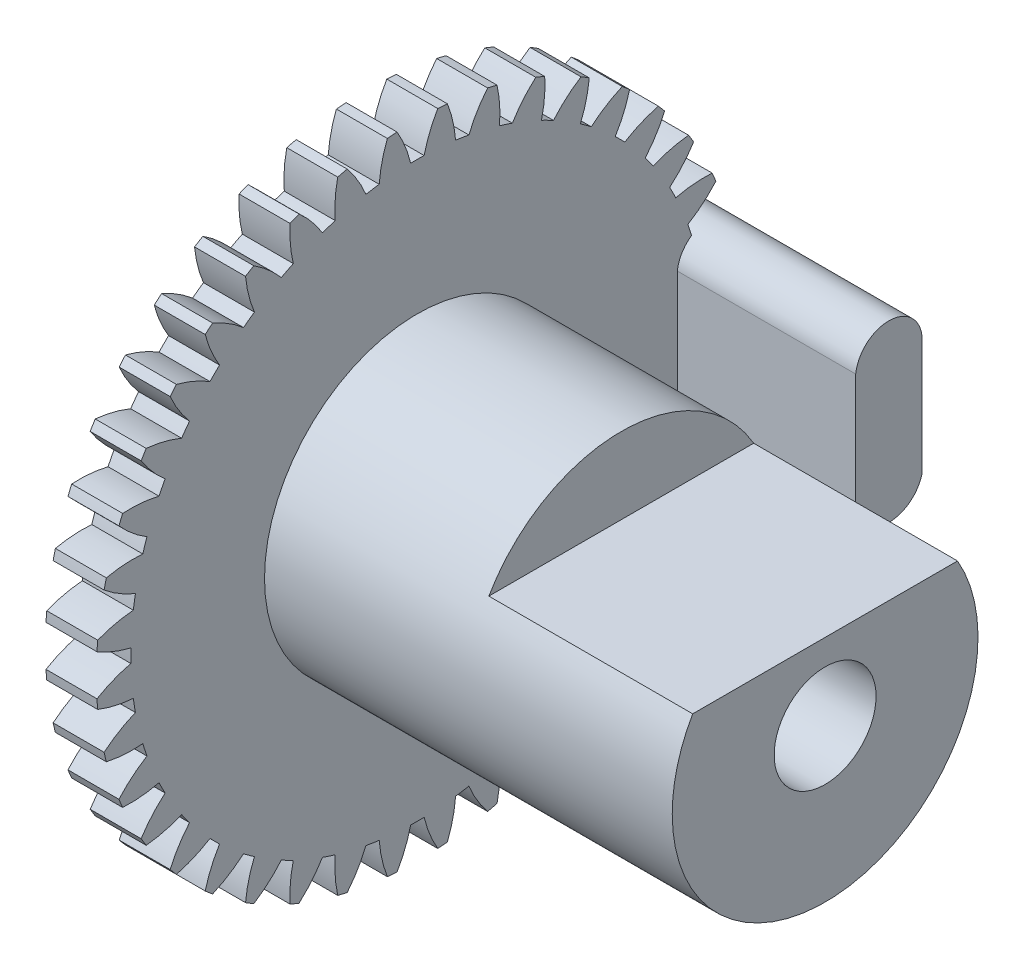
SolidWorks part; units mm, degrees
material "ABS PC"
ref_plane "Plane1" through (0, 0, 0) normal (0, 0, 1) x (1, 0, 0)
ref_plane "Plane2" through (0, 0, 0) normal (0, 1, 0) x (1, 0, 0)
ref_plane "Plane3" through (0, 0, 0) normal (1, 0, 0) x (0, 0, -1)
sketch "HoldingSke" plane through (0, 0, 0) normal (0, 1, 0) x (1, 0, 0)
  line L0 (0, 0) -> (2.5535, -2.1426)
  line L1 (-15, 0) -> (100, 0) construction
  line L2 (0, 0) -> (-2.1039, 2.3779)
  line L3 (0, 0) -> (-11.863, 4.5341)
  line L4 (0, 0) -> (6.6156, 5.5511)
  line L5 (0, 0) -> (-46.8476, -17.4728)
  line L6 (0, 0) -> (-0.829, -0.5593)
  line L7 (-2.1039, 2.3779) -> (8.6586, 51.2059)
  line L8 (-76.2, 54.61) -> (-75.9, 54.61)
  line L9 (-71.009, 38.7566) -> (-53.1078, 45.2721)
  line L10 (-76.2, 71.12) -> (104.1128, 71.12)
  line L11 (0, 0) -> (-1, 0)
  line L12 (-76.2, 101.6) -> (-76.19, 101.6)
  line L13 (24.9733, 27.94) -> (52.9518, 28.4284)
  line L14 (24.9733, 27.94) -> (24.9743, 27.94)
  line L15 (24.9733, 27.94) -> (100.4006, 29.5858)
  line L16 (-63.627, -0.3) -> (-12.827, -0.3)
  circle A0 centre (0, 0) radius 1
  circle A1 centre (0, 0) radius 5.624
  circle A2 centre (0, 0) radius 37.5
  circle A3 centre (0, 0) radius 1
  dimension "MHD" = 11.248
  dimension "Hub_dia" = 75
  dimension "Bore" = 2
  dimension "MBD" = 2
  dimension "Num_teeth" = 40
  dimension "Pitch" = 3.3333
  dimension "Overall_len" = 50
  dimension "Show_teeth" = 40
  dimension "Thickness" = 1
  dimension "OAL" = 50.0001
  dimension "T_dim" = 0.3
  dimension "Ap" = 20
  dimension "H" = 19.05
  dimension "Pitch_radius" = 180.3128
  dimension "Width" = 1
  dimension "Backlash" = 0.01
  dimension "Addendum_fac" = 1
  dimension "Dedendum_fac" = 1.25
  dimension "Clearance_fac" = 0.25
  dimension "Dedendum_add" = 0.001
  dimension "Module" = 0.3
sketch "BasProSke" plane through (0, 0, 0) normal (0, 1, 0) x (1, 0, 0)
  line L0 (-10, 0) -> (60, 0) construction
  line L1 (0, 0) -> (0, 6.3)
  line L2 (0, 0) -> (1, 0)
  line L3 (1, 0) -> (1, 6.3)
  line L4 (1, 6.3) -> (0, 6.3)
  dimension "Thickness" = 1
  dimension "Diameter" = 12.6
revolve "Base-Revolve" add sketch "BasProSke" angle 360 about L0
sketch "TooCutSke" plane through (0, 0, 0) normal (1, 0, 0) x (0, 0, -1)
  line L1 (0, 0) -> (0, 107) construction
  line L2 (0, 0) -> (-0.2531, 5.9947) construction
  line L3 (0, 0) -> (-0.9409, 11.9551) construction
  line L4 (-0.2531, 5.9947) -> (-0.4704, 5.9776) construction
  arc A0 (0.1321, 5.6224) -> (-0.1321, 5.6224) centre (0, 0) ccw
  arc A1 (0.4141, 6.3118) -> (-0.4141, 6.3118) centre (0, 0) ccw
  circle A2 centre (0, 0) radius 6 construction
  circle A3 centre (0, 0) radius 5.6382 construction
  arc A4 (-0.1321, 5.6224) -> (-0.4141, 6.3118) centre (-2.4676, 5.0695) ccw
  arc A5 (0.4141, 6.3118) -> (0.1321, 5.6224) centre (2.4676, 5.0695) ccw
  dimension "Root_dia" = 11.248
  dimension "Overcut_dia" = 12.6508
  dimension "Pitch_dia" = 12
  dimension "Base_dia" = 11.2763
  dimension "Flank_rad" = 2.4
  dimension "Half_ang" = 4.5
  dimension "Half_CT" = 0.2181
extrude "ToothCut" cut sketch "TooCutSke" along normal through all
fillet "Breaks" [suppressed] radius 0.006
fillet "RootFillets" [suppressed] radius 0.076
pattern_circular "TeethCuts" count 40 every 9 about axis through (-10, 0, 0) along (1, 0, 0) of "ToothCut", "RootFillets", "Breaks"
sketch "HubNeaOneSke" plane through (0, 0, 0) normal (-1, 0, 0) x (0, 0, 1)
  circle A0 centre (0, 0) radius 5.624
  dimension "Diameter" = 11.248
extrude "HubNearOne" [suppressed] add sketch "HubNeaOneSke" along normal blind 49.0001
sketch "HubNeaBotSke" plane through (0, 0, 0) normal (-1, 0, 0) x (0, 0, 1)
  circle A0 centre (0, 0) radius 5.624
  dimension "Diameter" = 11.248
extrude "HubNearBoth" [suppressed] add sketch "HubNeaBotSke" along normal blind 24.5
ref_plane "FarPln" through (1, 0, 0) normal (1, 0, 0) x (0, 0, -1)
sketch "HubFarSke" plane through (1, 0, 0) normal (1, 0, 0) x (0, 0, -1)
  circle A0 centre (0, 0) radius 5.624
  dimension "Diameter" = 11.248
extrude "HubFar" [suppressed] add sketch "HubFarSke" along normal blind 24.5
sketch "BorSke" plane through (0, 0, 0) normal (1, 0, 0) x (0, 0, -1)
  circle A0 centre (0, 0) radius 1
  dimension "Diameter" = 2
extrude "Bore" cut sketch "BorSke" along normal mid plane 100.0001
sketch "KeySke" plane through (0, 0, 0) normal (1, 0, 0) x (0, 0, -1)
  line L0 (-0.4, 0) -> (-0.4, 1.3)
  line L1 (-0.4, 1.3) -> (0.4, 1.3)
  line L2 (0.4, 1.3) -> (0.4, 0)
  line L3 (0, 0) -> (0, 34) construction
  line L4 (-0.4, 0) -> (0.4, 0)
  dimension "Offset" = 1.3
  dimension "Width" = 0.8
extrude "Keyway" [suppressed] cut sketch "KeySke" along normal mid plane 100.0001
pattern_circular "Keyway2" [suppressed] count 2 every 90 about axis through (-10, 0, 0) along (1, 0, 0)
sketch "Schizzo1" plane through (1, 0, 0) normal (1, 0, 0) x (0, 0, -1)
  circle A0 centre (0, 0) radius 1
  circle A1 centre (0, 0) radius 3
  circle A2 centre (0, 0) radius 1 construction
  dimension "D1" = 6
extrude "Estrusione-Estrusione1" add sketch "Schizzo1" along normal blind 8
sketch "Schizzo2" plane through (9, 0, 0) normal (1, 0, 0) x (0, 0, -1)
  line L0 (-2.5981, 1.5) -> (2.5981, 1.5)
  circle A0 centre (0, 0) radius 3 construction
  arc A1 (2.5981, 1.5) -> (-2.5981, 1.5) centre (0, 0) ccw
  dimension "D1" = 1.5
extrude "Taglio-Estrusione1" cut sketch "Schizzo2" against normal blind 4
sketch "Schizzo3" plane through (1, 0, 0) normal (1, 0, 0) x (0, 0, -1)
  line L0 (5.75, 1.1) -> (5.75, -1) construction
  line L1 (6.4, 1.1752) -> (6.4, -1.1752)
  line L2 (5.1, 1.1752) -> (5.1, -1.1752)
  line L4 (5.75, 0) -> (0, 0) construction
  arc A0 (6.4, 1.1752) -> (5.1, 1.1752) centre (5.75, 1.1) ccw
  arc A1 (5.1, -1.1752) -> (6.4, -1.1752) centre (5.75, -1) ccw
  point P16 (5.1, 0)
  dimension "D1" = 2.1
  dimension "D2" = 1.3
  dimension "D3" = 5.75
  dimension "D4" = 1
  dimension "D5" = 2.3505
extrude "Estrusione-Estrusione2" add sketch "Schizzo3" along normal blind 4.5 from surface at -1 starting at face at (0, 0, -1)
equation "' \"Module@HoldingSke\" = 6.35"
equation "' \"Num_teeth@HoldingSke\" = 12"
equation "' \"Ap@HoldingSke\" =  20"
equation "' \"Ap@HoldingSke\" = 20"
equation "' \"Width@HoldingSke\" = 0.5 * 25.4"
equation "' \"Hub_dia@HoldingSke\"= 1 * 25.4"
equation "' \"Hub_dia@HoldingSke\" = 1 * 25.4"
equation "' \"Overall_len@HoldingSke\" = 1.0 * 25.4"
equation "' \"Bore@HoldingSke\" = 0.75 * 25.4"
equation "' \"T_dim@HoldingSke\" = 0.1 * 25.4"
equation "' \"Width@KeySke\" = 0.25 * 25.4"
equation "' \"Show_teeth@HoldingSke\" = 13"
equation "' \"Backlash@HoldingSke\" = 0.009 * 25.4"
equation "' \"Addendum_fac@HoldingSke\" = 1.0"
equation "' \"Dedendum_fac@HoldingSke\" = 1.25"
equation "' \"Dedendum_add@HoldingSke\" = 0.00005 * 25.4"
equation "' \"Clearance_fac@HoldingSke\" = 0.25"
equation "\"Pitch@HoldingSke\" = 1 / \"Module@HoldingSke\""
equation "\"Overcut_dia@TooCutSke\" = (\"Num_teeth@HoldingSke\" + 2 * \"Addendum_fac@HoldingSke\") / \"Pitch@HoldingSke\" + 0.002 * 25.4"
equation "\"Pitch_dia@TooCutSke\" = \"Num_teeth@HoldingSke\" / \"Pitch@HoldingSke\""
equation "\"Base_dia@TooCutSke\" = \"Num_teeth@HoldingSke\" / \"Pitch@HoldingSke\" * cos((\"Ap@HoldingSke\"  * 3.14159265 / 180))"
equation "\"Root_dia@TooCutSke\" = (\"Num_teeth@HoldingSke\" + 2) / \"Pitch@HoldingSke\" - 2 * (\"Addendum_fac@HoldingSke\" + \"Dedendum_fac@HoldingSke\") / \"Pitch@HoldingSke\" - \"Dedendum_add@HoldingSke\" * 2"
equation "\"Half_ang@TooCutSke\" = 180 / \"Num_teeth@HoldingSke\""
equation "\"Half_CT@TooCutSke\" = \"Num_teeth@HoldingSke\" / \"Pitch@HoldingSke\" * sin((3.14159265 / 2 / \"Num_teeth@HoldingSke\")) / 2 - 7 * \"Backlash@HoldingSke\" / 4"
equation "\"Flank_rad@TooCutSke\" = \"Num_teeth@HoldingSke\" / \"Pitch@HoldingSke\" / 5"
equation "\"Radius@RootFillets\" = \"Clearance_fac@HoldingSke\" / \"Pitch@HoldingSke\" + \"Dedendum_add@HoldingSke\""
equation "\"Break_rad@Breaks\" = 0.02 / \"Pitch@HoldingSke\""
equation "\"Thickness@HoldingSke\" = \"Width@HoldingSke\""
equation "\"OAL@HoldingSke\" = \"Thickness@HoldingSke\""
equation "\"MHD@HoldingSke\" = (\"Num_teeth@HoldingSke\" + 2) / \"Pitch@HoldingSke\" - 2 * (\"Addendum_fac@HoldingSke\" + \"Dedendum_fac@HoldingSke\")  / \"Pitch@HoldingSke\" - \"Dedendum_add@HoldingSke\" * 2"
equation "\"MBD@HoldingSke\" = (\"Num_teeth@HoldingSke\" + 2) / \"Pitch@HoldingSke\" - 2 * (\"Addendum_fac@HoldingSke\" + \"Dedendum_fac@HoldingSke\")  / \"Pitch@HoldingSke\" - \"Dedendum_add@HoldingSke\" * 2 - 0.002 * 25.4"
equation "\"MHD@HoldingSke\" = ((sgn( \"MHD@HoldingSke\" - \"Hub_dia@HoldingSke\" )-1)*( \"MHD@HoldingSke\" - \"Hub_dia@HoldingSke\" ))/-2+ \"Hub_dia@HoldingSke\""
equation "\"MBD@HoldingSke\" = ((sgn( \"MBD@HoldingSke\" - \"Bore@HoldingSke\" )-1)*( \"MBD@HoldingSke\" - \"Bore@HoldingSke\" ))/-2+ \"Bore@HoldingSke\""
equation "\"OAL@HoldingSke\" = ((sgn( \"OAL@HoldingSke\" - \"Overall_len@HoldingSke\" )+1)*( \"OAL@HoldingSke\" - \"Overall_len@HoldingSke\" ))/2 + \"Overall_len@HoldingSke\" + 0.000002 * 25.4"
equation "\"Num_teeth@TeethCuts\" = int( \"Show_teeth@HoldingSke\" ) + 1"
equation "\"Num_teeth@TeethCuts\" = ((sgn( \"Num_teeth@TeethCuts\" - \"Num_teeth@HoldingSke\" )-1)*( \"Num_teeth@TeethCuts\" - \"Num_teeth@HoldingSke\" ))/-2+ \"Num_teeth@HoldingSke\""
equation "\"Num_teeth@TeethCuts\" = ((sgn( \"Num_teeth@TeethCuts\" - 2.0)+1)*( \"Num_teeth@TeethCuts\" - 2.0))/2 +2.0"
equation "\"Angle@TeethCuts\" = 360.0 / \"Num_teeth@HoldingSke\""
equation "\"Diameter@BasProSke\" = (\"Num_teeth@HoldingSke\" + 2 * \"Addendum_fac@HoldingSke\") / \"Pitch@HoldingSke\""
equation "\"Thickness@BasProSke\"  = \"Thickness@HoldingSke\""
equation "' \"Fillet_rad@BasProSke\" =  \"Thickness@HoldingSke\" * 0.05"
equation "' \"Fillet_rad@BasProSke\" = \"Thickness@HoldingSke\" * 0.05"
equation "\"MHD@HoldingSke\" = ((sgn( \"MHD@HoldingSke\" - \"Root_dia@TooCutSke\" )-1)*( \"MHD@HoldingSke\" - \"Root_dia@TooCutSke\" ))/-2+ \"Root_dia@TooCutSke\""
equation "\"Diameter@HubNeaOneSke\" = \"MHD@HoldingSke\""
equation "\"Length@HubNearOne\" = \"OAL@HoldingSke\" - \"Thickness@BasProSke\""
equation "\"Diameter@HubNeaBotSke\" = \"MHD@HoldingSke\""
equation "\"Length@HubNearBoth\" = ( \"OAL@HoldingSke\" - \"Thickness@BasProSke\" ) / 2.0"
equation "\"Thickness@FarPln\" = \"Thickness@BasProSke\""
equation "\"Diameter@HubFarSke\" = \"MHD@HoldingSke\""
equation "\"Length@HubFar\" = ( \"OAL@HoldingSke\" - \"Thickness@BasProSke\" ) / 2.0"
equation "\"Diameter@BorSke\" = \"MBD@HoldingSke\""
equation "\"D1@Bore\" = \"OAL@HoldingSke\" * 2.0"
equation "\"D1@Keyway\" = \"OAL@HoldingSke\" * 2.0"
equation "\"Offset@KeySke\" = \"T_dim@HoldingSke\" + \"MBD@HoldingSke\" / 2.0"
